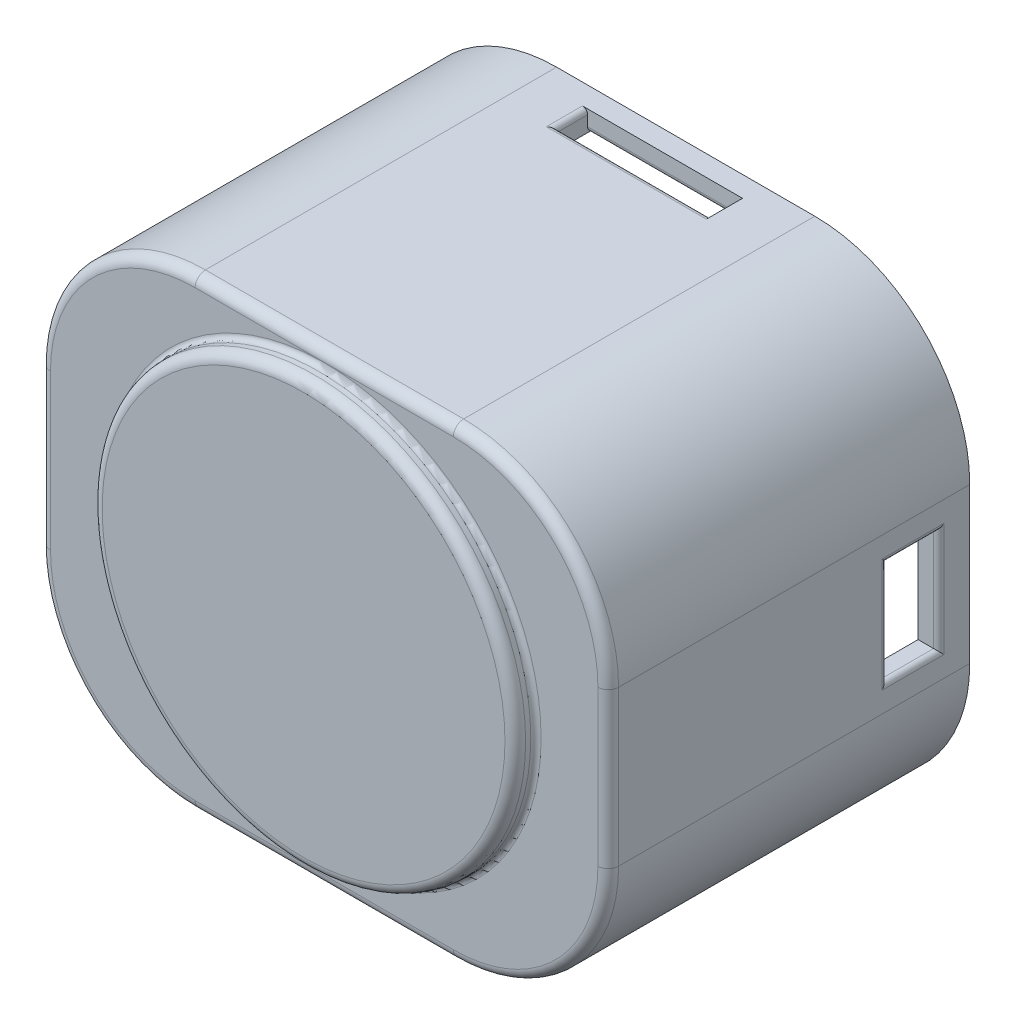
SolidWorks part; units mm, degrees
ref_plane "정면" through (0, 0, 0) normal (0, 0, 1) x (1, 0, 0)
ref_plane "윗면" through (0, 0, 0) normal (0, 1, 0) x (1, 0, 0)
ref_plane "우측면" through (0, 0, 0) normal (1, 0, 0) x (0, 0, -1)
sketch "스케치1" plane through (0, 0, 0) normal (0, 0, 1) x (1, 0, 0)
  line L1 (-23.6271, 17.3639) -> (31.3729, 17.3639)
  line L2 (-23.6271, 17.3639) -> (-23.6271, -27.6361)
  line L3 (-23.6271, -27.6361) -> (31.3729, -27.6361)
  line L4 (31.3729, 17.3639) -> (31.3729, -27.6361)
  dimension "D1" = 55
  dimension "D2" = 45
extrude "보스-돌출1" add sketch "스케치1" along normal blind 35
sketch "스케치4" plane through (-2.1642, -3.487, 35) normal (0, 0, 1) x (1, 0, 0)
  line L2 (33.5371, -24.1491) -> (33.5371, 20.8509) construction
  circle A0 centre (6.0371, -1.1717) radius 20.5
  point P2 (6.612, -1.1717)
  point P4 (0, 0)
  point P7 (11.0371, -1.6491)
  point P8 (11.0371, -1.6491)
  point P9 (0, 0)
  point P10 (11.0371, -1.6491)
  dimension "D1" = 41
  dimension "D2" = 27.5
extrude "보스-돌출3" add sketch "스케치4" along normal blind 2
fillet "필렛2" radius 15 1 edges at (31.3729, 17.3639, 17.5)
fillet "필렛3" radius 15 3 edges at (-23.6271, -27.6361, 17.5) (31.3729, -27.6361, 17.5) (-23.6271, 17.3639, 17.5)
sketch "스케치5" plane through (-2.1642, -3.487, 37) normal (0, 0, 1) x (1, 0, 0)
fillet "필렛4" radius 1 8 edges at (3.8729, 17.3639, 35) (26.9795, 12.9705, 35) (31.3729, -5.1361, 35) (26.9795, -23.2427, 35) (3.8729, -27.6361, 35) (-19.2337, -23.2427, 35) (-23.6271, -5.1361, 35) (-19.2337, 12.9705, 35)
shell "쉘1" thickness 2
sketch "스케치6" plane through (0, 0, 33) normal (0, 0, -1) x (-1, 0, 0)
sketch "스케치7" plane through (0, 0, 33) normal (0, 0, -1) x (-1, 0, 0)
  circle A1 centre (-3.8729, -4.6587) radius 20.5
  circle A2 centre (-3.8729, -4.6587) radius 21.5
  dimension "D1" = 41
  dimension "D2" = 1
extrude "보스-돌출4" add sketch "스케치7" along normal blind 5
fillet "필렛5" radius 1 1 edges at (24.3729, -4.6587, 37)
fillet "필렛6" radius 0.5 1 edges at (24.3729, -4.6587, 35)
sketch "스케치8" plane through (31.3729, 0, 0) normal (1, 0, 0) x (0, 0, -1)
  line L0 (-34, -5.1361) -> (0, -5.1361) construction
  line L1 (-34, 2.3639) -> (-34, -12.6361) construction
  line L2 (0, -12.6361) -> (0, 2.3639) construction
  line L3 (-17, 2.3639) -> (-17, -12.6361) construction
  line L4 (0, 2.3639) -> (-34, 2.3639) construction
  line L5 (-34, -12.6361) -> (0, -12.6361) construction
  line L7 (-8, -0.1361) -> (-3, -0.1361)
  line L8 (-8, -0.1361) -> (-8, -10.1361)
  line L9 (-8, -10.1361) -> (-3, -10.1361)
  line L10 (-3, -0.1361) -> (-3, -10.1361)
  line L11 (-8, -0.1361) -> (-3, -10.1361) construction
  line L12 (-8, -10.1361) -> (-3, -0.1361) construction
  point P12 (-5.5, -5.1361)
  dimension "D1" = 5
  dimension "D2" = 10
  dimension "D3" = 3
extrude "컷-돌출1" cut sketch "스케치8" against normal up to next
sketch "스케치13" plane through (0, 0, 35) normal (0, 0, 1) x (1, 0, 0)
sketch "스케치14" plane through (0, 17.3639, 0) normal (0, 1, 0) x (1, 0, 0)
  line L0 (3.8729, 0) -> (3.8729, -34) construction
  line L1 (16.3729, 0) -> (-8.6271, 0) construction
  line L2 (-8.6271, -34) -> (16.3729, -34) construction
  line L4 (-3.6271, -2) -> (11.3729, -2)
  line L5 (-3.6271, -2) -> (-3.6271, -5)
  line L6 (-3.6271, -5) -> (11.3729, -5)
  line L7 (11.3729, -2) -> (11.3729, -5)
  line L8 (-3.6271, -2) -> (11.3729, -5) construction
  line L9 (-3.6271, -5) -> (11.3729, -2) construction
  point P6 (3.8729, -3.5)
  dimension "D1" = 15
  dimension "D2" = 3
  dimension "D3" = 2
extrude "컷-돌출2" cut sketch "스케치14" against normal up to next
sketch "스케치17" plane through (0, -27.6361, 0) normal (0, -1, 0) x (1, 0, 0)
  line L0 (3.8729, 34) -> (3.8729, 0) construction
  line L1 (16.3729, 34) -> (-8.6271, 34) construction
  line L2 (-8.6271, 0) -> (16.3729, 0) construction
  line L4 (-3.6271, 5) -> (11.3729, 5)
  line L5 (-3.6271, 5) -> (-3.6271, 2)
  line L6 (-3.6271, 2) -> (11.3729, 2)
  line L7 (11.3729, 5) -> (11.3729, 2)
  line L8 (-3.6271, 5) -> (11.3729, 2) construction
  line L9 (-3.6271, 2) -> (11.3729, 5) construction
  point P6 (3.8729, 3.5)
  dimension "D1" = 15
  dimension "D2" = 3
  dimension "D3" = 2
extrude "컷-돌출3" cut sketch "스케치17" against normal up to next contours L5 L4 L7 L6
fillet "필렛9" radius 0.5 12 edges at (3.8729, -27.6361, 2) (11.3729, -27.6361, 3.5) (-3.6271, -27.6361, 3.5) (3.8729, -27.6361, 5) (31.3729, -10.1361, 5.5) (31.3729, -5.1361, 3) (31.3729, -0.1361, 5.5) (31.3729, -5.1361, 8) (11.3729, 15.3639, 3.5) (3.8729, 15.3639, 2) (-3.6271, 17.3639, 3.5) (3.8729, 17.3639, 5)
